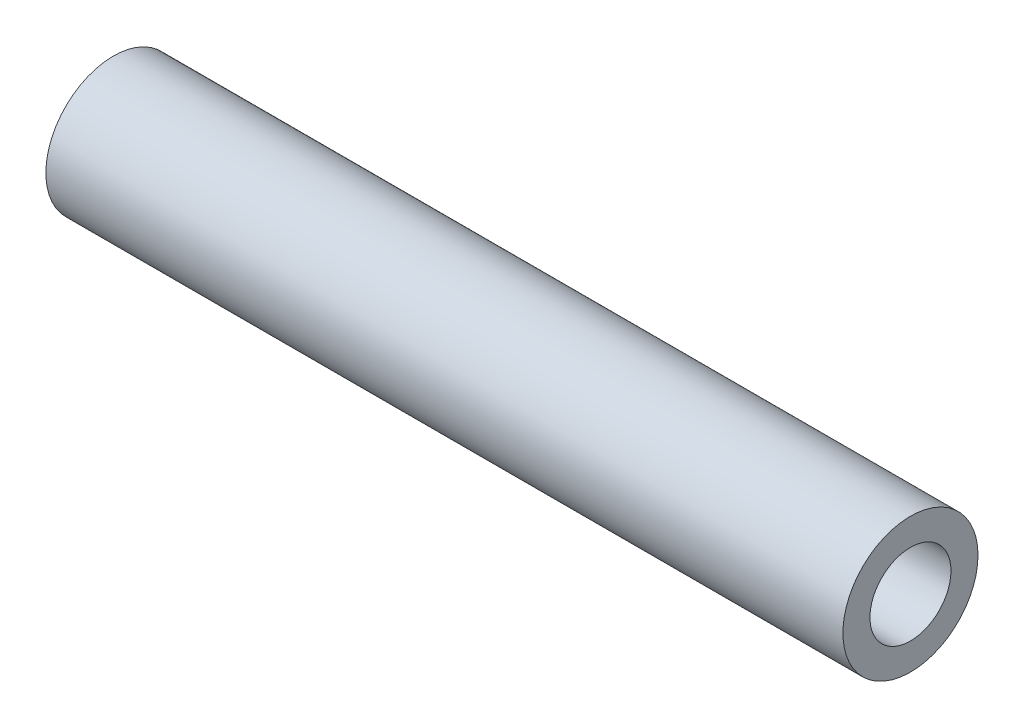
SolidWorks part; units mm, degrees
ref_plane "Front Plane" through (0, 0, 0) normal (0, 0, 1) x (1, 0, 0)
ref_plane "Top Plane" through (0, 0, 0) normal (0, 1, 0) x (1, 0, 0)
ref_plane "Right Plane" through (0, 0, 0) normal (1, 0, 0) x (0, 0, -1)
sketch "Sketch1" plane through (0, 0, 0) normal (1, 0, 0) x (0, 0, -1)
  circle A0 centre (0, 0) radius 2.5
  circle A1 centre (0, 0) radius 1.5
  dimension "D1" = 5
  dimension "D2" = 3
extrude "Boss-Extrude1" add sketch "Sketch1" along normal blind 29.5
